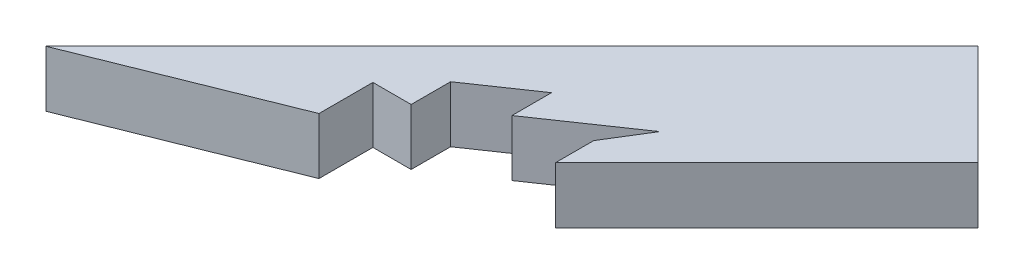
SolidWorks part; units mm, degrees
ref_plane "Front Plane" through (0, 0, 0) normal (0, 0, 1) x (1, 0, 0)
ref_plane "Top Plane" through (0, 0, 0) normal (0, 1, 0) x (1, 0, 0)
ref_plane "Right Plane" through (0, 0, 0) normal (1, 0, 0) x (0, 0, -1)
sketch "Sketch1" plane through (0, 0, 0) normal (0, 1, 0) x (1, 0, 0)
  line L0 (-112.5044, -43.3161) -> (-7.448, 61.7402)
  line L1 (-7.448, 61.7402) -> (15.288, 39.0041)
  line L2 (15.288, 39.0041) -> (-32.3401, -8.624)
  line L3 (-32.3401, -8.624) -> (-32.3401, 0)
  line L4 (-32.3401, 0) -> (-26.6561, 9.212)
  line L5 (-26.6561, 9.212) -> (-46.4521, -4.312)
  line L6 (-46.4521, -4.312) -> (-46.4521, 4.606)
  line L7 (-46.4521, 4.606) -> (-59.9762, -4.6332)
  line L8 (-59.9762, -4.6332) -> (-59.9762, -13.524)
  line L9 (-59.9762, -13.524) -> (-68.6002, -13.524)
  line L10 (-68.6002, -13.524) -> (-68.6002, -25.6761)
  line L11 (-68.6002, -25.6761) -> (-112.5044, -43.3161)
extrude "Boss-Extrude1" add sketch "Sketch1" along normal blind 12.7
